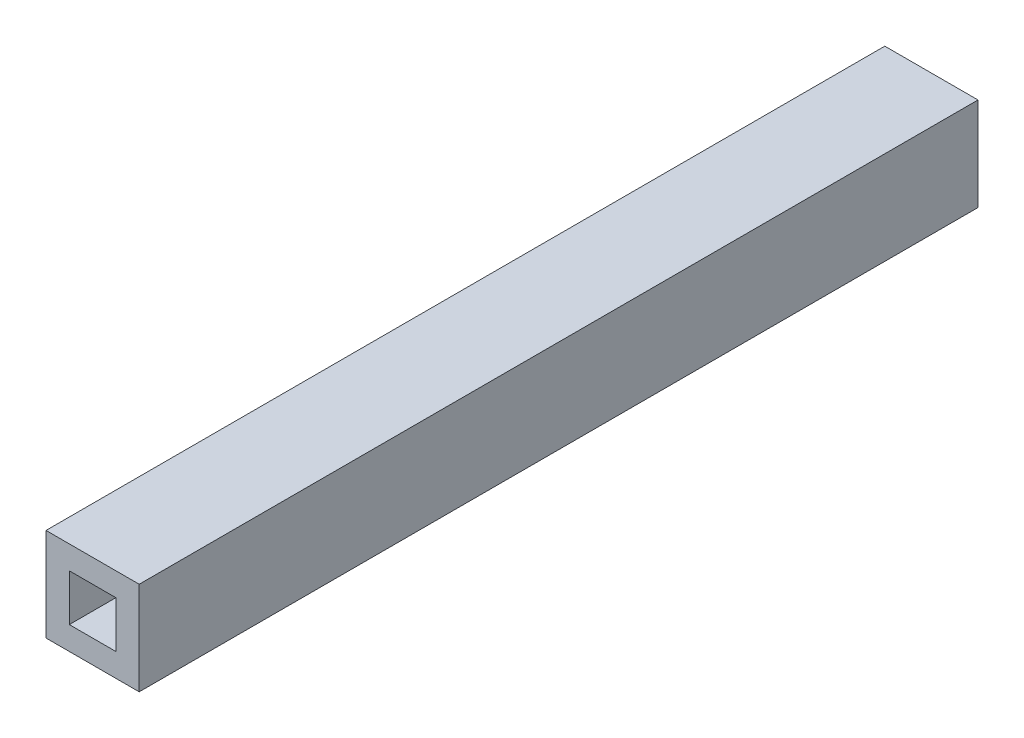
SolidWorks part; units mm, degrees
material "6063-O"
ref_plane "Front Plane" through (0, 0, 0) normal (0, 0, 1) x (1, 0, 0)
ref_plane "Top Plane" through (0, 0, 0) normal (0, 1, 0) x (1, 0, 0)
ref_plane "Right Plane" through (0, 0, 0) normal (1, 0, 0) x (0, 0, -1)
sketch "Sketch1" plane through (0, 0, 0) normal (0, 0, 1) x (1, 0, 0)
  line L1 (-10, -10) -> (10, -10)
  line L2 (-10, -10) -> (-10, 10)
  line L3 (-10, 10) -> (10, 10)
  line L4 (10, -10) -> (10, 10)
  line L5 (-10, -10) -> (10, 10) construction
  line L6 (-10, 10) -> (10, -10) construction
  point P0 (0, 0)
  dimension "D1" = 20
extrude "Extrude-Thin1" add sketch "Sketch1" along normal blind 180 thin thin type one direction reverse wall 5
